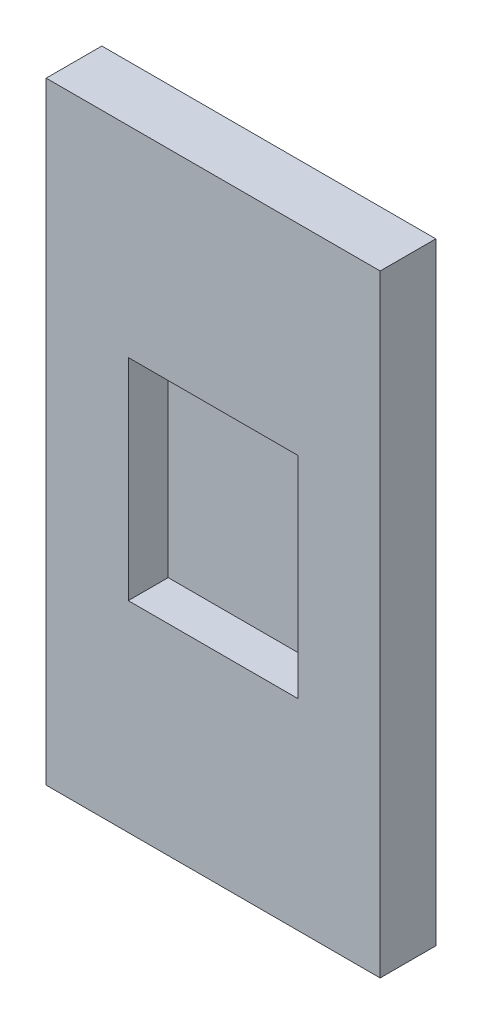
SolidWorks part; units mm, degrees
ref_plane "정면" through (0, 0, 0) normal (0, 0, 1) x (1, 0, 0)
ref_plane "윗면" through (0, 0, 0) normal (0, 1, 0) x (1, 0, 0)
ref_plane "우측면" through (0, 0, 0) normal (1, 0, 0) x (0, 0, -1)
sketch "스케치1" plane through (0, 0, 0) normal (0, 0, 1) x (1, 0, 0)
  line L1 (-9, -16.5) -> (9, -16.5)
  line L2 (-9, -16.5) -> (-9, 16.5)
  line L3 (-9, 16.5) -> (9, 16.5)
  line L4 (9, -16.5) -> (9, 16.5)
  line L5 (-9, -16.5) -> (9, 16.5) construction
  line L6 (-9, 16.5) -> (9, -16.5) construction
  point P0 (0, 0)
  dimension "D1" = 18
  dimension "D2" = 33
extrude "보스-돌출1" add sketch "스케치1" along normal blind 3
sketch "스케치2" plane through (0, 0, 3) normal (0, 0, 1) x (1, 0, 0)
  line L1 (-4.575, -5.675) -> (4.575, -5.675)
  line L2 (-4.575, -5.675) -> (-4.575, 5.675)
  line L3 (-4.575, 5.675) -> (4.575, 5.675)
  line L4 (4.575, -5.675) -> (4.575, 5.675)
  line L5 (-4.575, -5.675) -> (4.575, 5.675) construction
  line L6 (-4.575, 5.675) -> (4.575, -5.675) construction
  point P1 (0, 0)
  dimension "D1" = 9.15
  dimension "D2" = 11.35
extrude "컷-돌출1" cut sketch "스케치2" against normal blind 2.15
